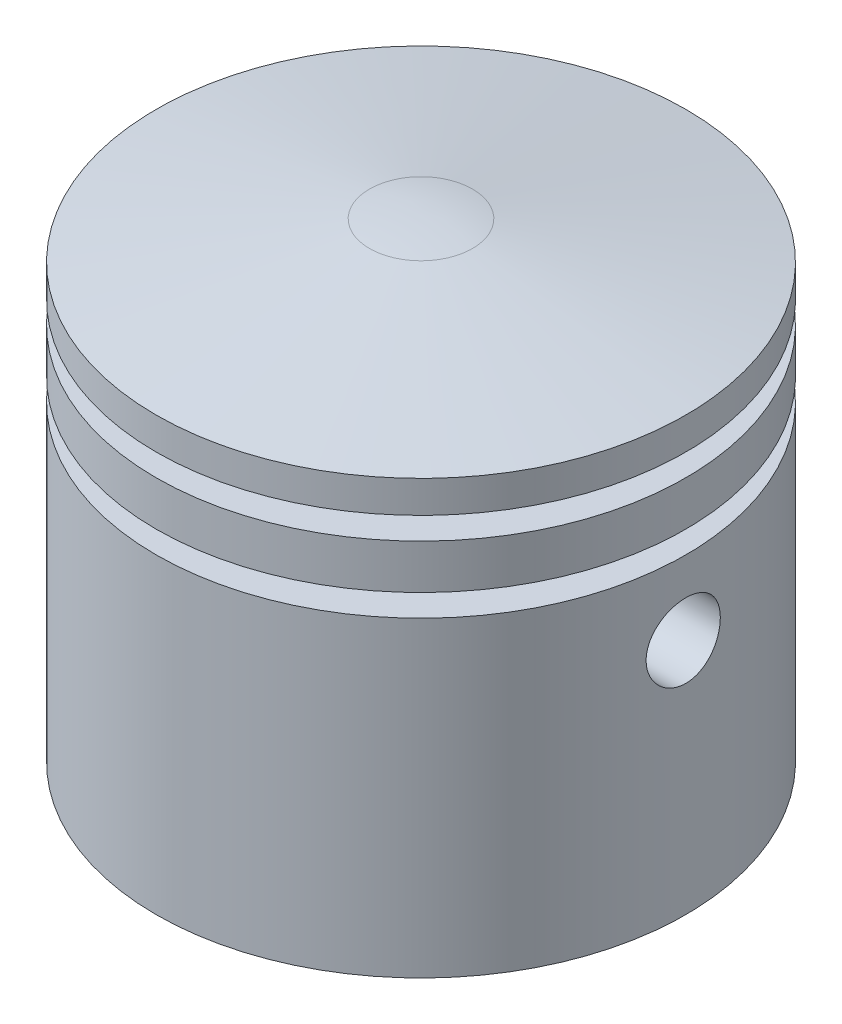
SolidWorks part; units mm, degrees
ref_plane "Front Plane" through (0, 0, 0) normal (0, 0, 1) x (1, 0, 0)
ref_plane "Top Plane" through (0, 0, 0) normal (0, 1, 0) x (1, 0, 0)
ref_plane "Right Plane" through (0, 0, 0) normal (1, 0, 0) x (0, 0, -1)
sketch "Sketch2" plane through (0, 0, 0) normal (0, 0, 1) x (1, 0, 0)
  line L0 (0, 24.7604) -> (0, -26.1118) construction
  line L2 (14.152, -12.8967) -> (14.152, 10.226) construction
  line L4 (-17.848, -12.8967) -> (-17.848, 16.2648)
  line L5 (14.152, -12.8967) -> (-17.848, 16.2648) construction
  line L6 (14.152, 10.226) -> (-17.848, -12.8967) construction
  line L7 (-17.848, 16.2648) -> (-3.473, 18.7995)
  line L8 (-13, -12.8967) -> (-13, -2.8967)
  line L9 (-3.473, 18.7995) -> (-0.2786, 18.7995) construction
  line L10 (-13, -2.8967) -> (-10, -2.8967)
  line L11 (-10, -2.8967) -> (-10, 11.1033)
  line L12 (-10, 11.1033) -> (0, 11.1033)
  line L13 (-17.848, 9.6033) -> (-14.5, 9.6033)
  line L14 (-14.5, 9.6033) -> (-14.5, 8.1033)
  line L15 (-14.5, 8.1033) -> (-17.848, 8.1033)
  line L16 (-17.848, 14.1033) -> (-14.5, 14.1033)
  line L17 (-14.5, 14.1033) -> (-14.5, 12.6033)
  line L18 (-14.5, 12.6033) -> (-17.848, 12.6033)
  line L19 (-13, -12.8967) -> (-17.848, -12.8967)
  line L20 (0, 19.1033) -> (0, 11.1033)
  arc A0 (-3.473, 18.7995) -> (0, 19.1033) centre (0, -0.8967) cw
  point P0 (0, 0)
  point P21 (-16.174, 9.6033)
  dimension "D12" = 20
  dimension "D2" = 21
  dimension "D3" = 10
  dimension "D4" = 32
  dimension "D6" = 10
  dimension "D7" = 13
  dimension "D8" = 1.5
  dimension "D9" = 3
  dimension "D10" = 14.5
revolve "Revolve1" add sketch "Sketch2" angle 360 about L0
sketch "Sketch3" plane through (0, 0, 0) normal (1, 0, 0) x (0, 0, -1)
  line L0 (0, -12.8967) -> (0, 8.1033) construction
  line L1 (0, 9.6033) -> (0, 12.6033) construction
  line L2 (-17.848, -12.8967) -> (17.848, -12.8967) construction
  circle A0 centre (0, 3.1033) radius 2.5
  dimension "D1" = 5
  dimension "D2" = 16
extrude "Cut-Extrude1" cut sketch "Sketch3" against normal through all both and the other way through all
